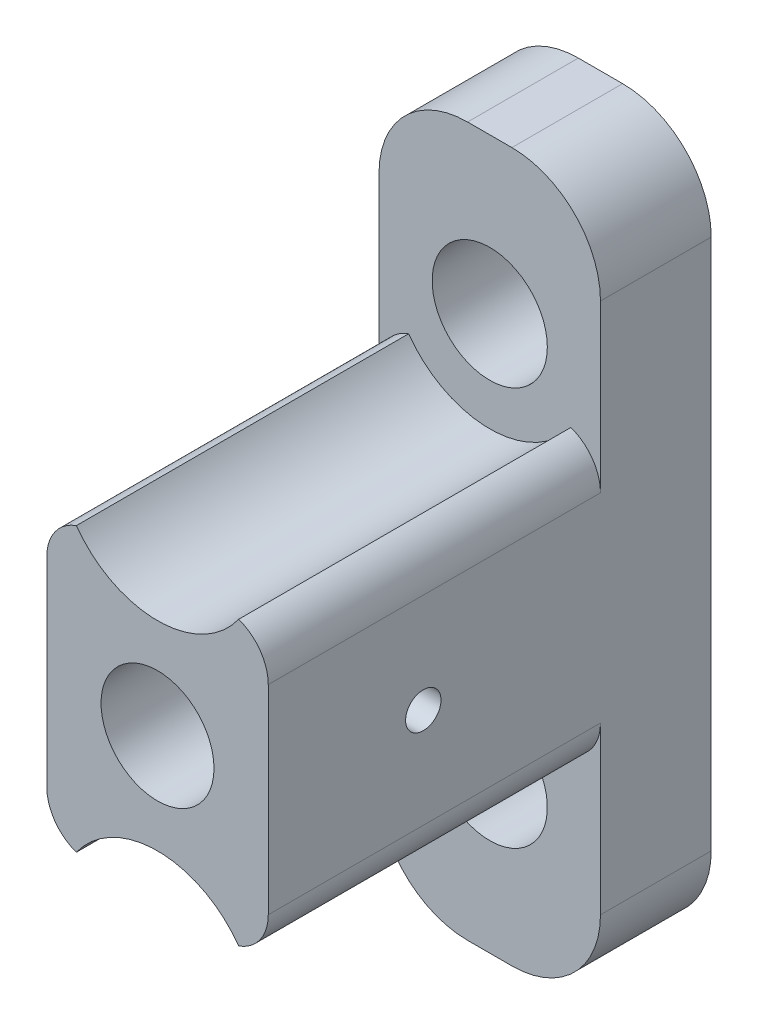
SolidWorks part; units mm, degrees
ref_plane "Front Plane" through (0, 0, 0) normal (0, 0, 1) x (1, 0, 0)
ref_plane "Top Plane" through (0, 0, 0) normal (0, 1, 0) x (1, 0, 0)
ref_plane "Right Plane" through (0, 0, 0) normal (1, 0, 0) x (0, 0, -1)
sketch "Sketch1" plane through (0, 0, 0) normal (0, 0, 1) x (1, 0, 0)
  line L0 (0, 16) -> (0, 0) construction
  line L5 (-5, 0) -> (5, 0) construction
  line L8 (-5, -12) -> (-5, 12)
  line L9 (-1, 16) -> (1, 16)
  line L10 (-1, -16) -> (1, -16)
  line L11 (5, -12) -> (5, 12)
  circle A2 centre (0, 9) radius 2.6
  circle A6 centre (0, -9) radius 2.6
  arc A8 (-5, 12) -> (-1, 16) centre (-1, 12) cw
  arc A9 (-5, -12) -> (-1, -16) centre (-1, -12) ccw
  arc A10 (5, -12) -> (1, -16) centre (1, -12) cw
  arc A11 (5, 12) -> (1, 16) centre (1, 12) ccw
  point P22 (0, -16)
  dimension "D1" = 9
  dimension "D2" = 5.2
  dimension "D6" = 4
  dimension "D3" = 5
  dimension "D5" = 4
  dimension "3.5" = 7
extrude "Boss-Extrude1" add sketch "Sketch1" against normal blind 5
sketch "Sketch2" plane through (0, 0, 0) normal (0, 0, 1) x (1, 0, 0)
  line L0 (5, -12) -> (5, 12) construction
  line L1 (-5, -6.5) -> (5, -6.5)
  line L2 (-5, -6.5) -> (-5, 6.5)
  line L3 (-5, 6.5) -> (5, 6.5)
  line L4 (5, -6.5) -> (5, 6.5)
  line L5 (-5, -6.5) -> (5, 6.5) construction
  line L6 (-5, 6.5) -> (5, -6.5) construction
  circle A0 centre (0, 0) radius 2.55
  dimension "D1" = 6.5
  dimension "D2" = 5.1
sketch "Sketch3" plane through (0, 0, 0) normal (0, 0, 1) x (1, 0, 0)
ref_plane "Plane1" through (0, 0, 0) normal (0, 1, 0) x (1, 0, 0)
sketch "Sketch4" plane through (0, 0, 0) normal (0, 1, 0) x (1, 0, 0)
  circle A0 centre (0, -8) radius 0.8
  dimension "D2" = 1.6
  dimension "8" = 8
extrude "Boss-Extrude3" add sketch "Sketch2" along normal blind 15
fillet "Fillet2" radius 2 4 edges at (5, -6.5, 7.5) (-5, -6.5, 7.5) (5, 6.5, 7.5) (-5, 6.5, 7.5)
ref_plane "Plane3" through (0, 0, 15) normal (0, 0, 1) x (1, 0, 0)
sketch "Sketch6" plane through (0, 0, 15) normal (0, 0, 1) x (1, 0, 0)
  line L0 (-5, 0) -> (5, 0) construction
  line L1 (-5, 4.5) -> (-5, -4.5) construction
  line L2 (5, -4.5) -> (5, 4.5) construction
  line L3 (0, 0) -> (0, 9) construction
  circle A0 centre (0, 9) radius 4.5
  circle A1 centre (0, -9) radius 4.5
  dimension "D1" = 9
extrude "Cut-Extrude2" cut sketch "Sketch6" against normal up to surface (15 mm away) up to face at (0, 9.8585, 0)
ref_plane "Plane4" through (5, 0, 0) normal (1, 0, 0) x (0, 0, -1)
sketch "Sketch7" plane through (5, 0, 0) normal (1, 0, 0) x (0, 0, -1)
  circle A0 centre (-8, 0) radius 0.8
  dimension "D1" = 1.6
  dimension "D2" = 8
extrude "Cut-Extrude3" cut sketch "Sketch7" against normal through all both and the other way through all
